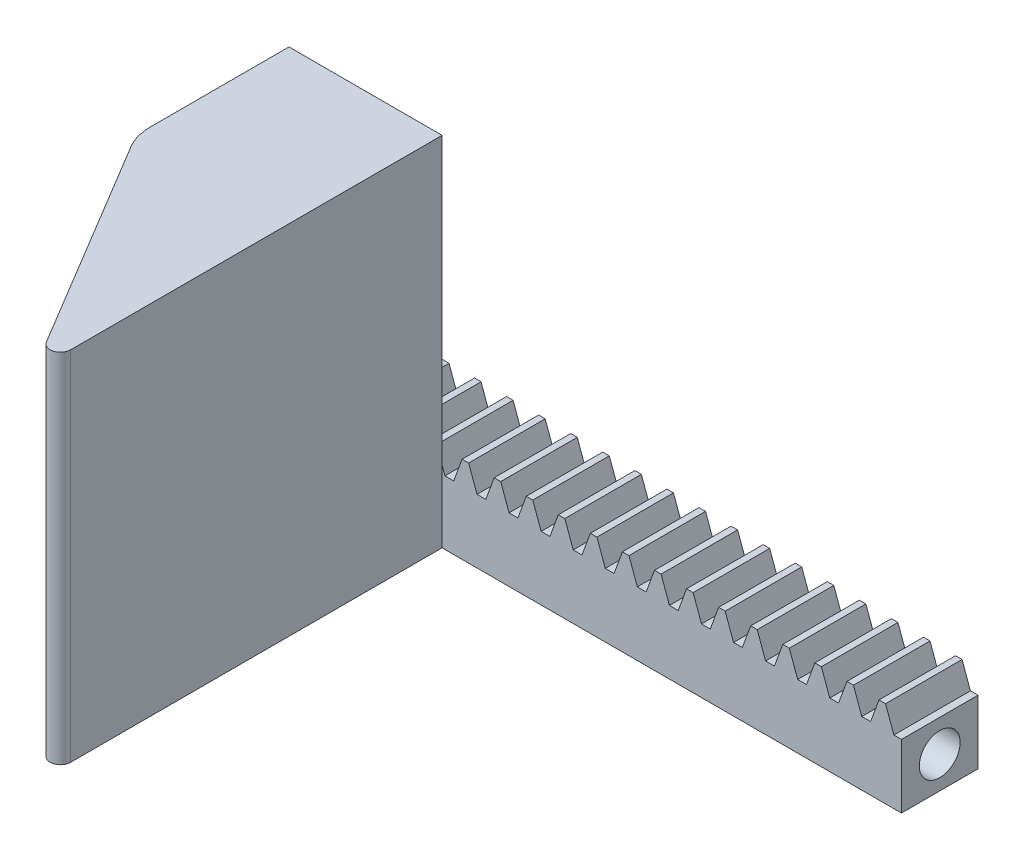
SolidWorks part; units mm, degrees
extrude "Blank" add sketch "BlankSke" against normal blind 15
sketch "BlankSke" plane through (0, 0, 0) normal (0, 0, 1) x (1, 0, 0)
  line L1 (0, 0) -> (120, 0)
  line L2 (0, 0) -> (0, 17)
  line L3 (0, 17) -> (120, 17)
  line L4 (120, 0) -> (120, 17)
  dimension "Length" = 120
  dimension "Blank_height" = 17
ref_plane "Plane1" through (0, 0, 0) normal (0, 0, 1) x (1, 0, 0)
ref_plane "Plane2" through (0, 0, 0) normal (0, 1, 0) x (1, 0, 0)
ref_plane "Plane3" through (0, 0, 0) normal (1, 0, 0) x (0, 0, -1)
other "Configuration Table"
sketch "HoldingSke" plane through (0, 0, 0) normal (0, 1, 0) x (1, 0, 0)
  line L0 (0, 0) -> (0.0696, 0.4951)
  line L1 (-15, 0) -> (100, 0) construction
  line L2 (0, 0) -> (-2.1039, 2.3779)
  line L3 (0, 0) -> (-11.863, 4.5341)
  line L4 (0, 0) -> (8.0624, 3.0949)
  line L5 (0, 0) -> (-23.7986, -8.8762)
  line L6 (0, 0) -> (-10.5278, -7.1032)
  line L9 (-71.009, 38.7566) -> (41.7541, 79.799)
  line L10 (-76.2, 4.3779) -> (-61.2, 4.3779)
  line L11 (0, 0) -> (-15, 0)
  line L12 (-76.2, 101.6) -> (-76.133, 101.6)
  line L13 (24.9733, 27.94) -> (52.9518, 28.4284)
  line L14 (24.9733, 27.94) -> (24.9743, 27.94)
  line L15 (24.9733, 27.94) -> (100.4006, 29.5858)
  circle A0 centre (0, 0) radius 19.05
  circle A1 centre (0, 0) radius 7.5
  circle A2 centre (0, 0) radius 12.7
  dimension "MPH" = 15
  dimension "Diameter" = 38.1
  dimension "Num_teeth" = 21
  dimension "Pitch" = 0.5
  dimension "Show_teeth" = 998
  dimension "Thickness" = 12.7
  dimension "Ap" = 20
  dimension "Pitch_height" = 15
  dimension "Width" = 15
  dimension "Backlash" = 0.067
  dimension "Addendum_fac" = 1
  dimension "Dedendum_fac" = 1.25
  dimension "Clearance_fac" = 0.25
  dimension "Dedendum_add" = 0.001
  dimension "Length" = 120
  dimension "Module" = 2
sketch "TooCutSkeIll" plane through (0, 0, 0) normal (0, 0, 1) x (1, 0, 0)
  line L0 (-2.4806, 16.9474) -> (-0.9819, 12.8296)
  line L1 (-0.5111, 12.5) -> (0.5111, 12.5)
  line L2 (0.9819, 12.8296) -> (2.4806, 16.9474)
  line L3 (120, 17) -> (0, 17) construction
  line L4 (0, 0) -> (0, 64.897) construction
  line L5 (-13.208, 15) -> (12.954, 15) construction
  line L6 (0, 0) -> (120, 0) construction
  line L7 (1.7718, 15) -> (1.7718, 48.7463) construction
  line L8 (-1.7718, 15) -> (-1.7718, 48.7463) construction
  line L9 (2.5558, 17) -> (2.5558, 17.0254)
  line L10 (-2.5558, 17) -> (-2.5558, 17.0254)
  line L11 (-2.5558, 17.0254) -> (2.5558, 17.0254)
  arc A0 (0.5111, 12.5) -> (0.9819, 12.8296) centre (0.5111, 13.001) ccw
  arc A1 (-0.9819, 12.8296) -> (-0.5111, 12.5) centre (-0.5111, 13.001) ccw
  arc A2 (2.5558, 17) -> (2.4806, 16.9474) centre (2.5558, 16.92) ccw
  arc A3 (-2.4806, 16.9474) -> (-2.5558, 17) centre (-2.5558, 16.92) ccw
  dimension "Pitch_height" = 15
  dimension "Addendum_plus" = 2.0254
  dimension "Pressure_angle" = 20
  dimension "Gap_width" = 3.5436
  dimension "Dedendum" = 2.5
extrude "ToothCutIll" [suppressed] cut sketch "TooCutSkeIll" against normal through all
sketch "TooCutSkeSim" plane through (0, 0, 0) normal (0, 0, 1) x (1, 0, 0)
  line L0 (0.8619, 12.5) -> (-0.8619, 12.5)
  line L1 (2.509, 17.0254) -> (0.8619, 12.5)
  line L2 (0, 17.4625) -> (0, 53.467) construction
  line L3 (2.509, 17.0254) -> (-2.509, 17.0254)
  line L6 (-2.509, 17.0254) -> (-0.8619, 12.5)
  line L9 (-1.7718, 15) -> (1.7718, 15) construction
  line L10 (0, 0) -> (120, 0) construction
  line L11 (1.7718, 15) -> (1.7718, 53.467) construction
  line L12 (-1.7718, 15) -> (-1.7718, 53.467) construction
  dimension "Pitch_height" = 15
  dimension "Addendum_plus" = 2.0254
  dimension "Pressure_angle" = 20
  dimension "Gap_width" = 3.5436
  dimension "Dedendum" = 2.5
extrude "ToothCutSim" cut sketch "TooCutSkeSim" against normal through all
pattern_linear "TeethCuts" count 20 spacing 6.2832 along (1, 0, 0) of "ToothCutIll", "ToothCutSim"
sketch "Esboço5" plane through (0, 0, 0) normal (0, -1, 0) x (1, 0, 0)
  line L0 (0, 0) -> (30, 0)
  line L1 (30, 0) -> (30, 72.7794)
  line L2 (26.285, 73.8084) -> (1.4251, 32.3751)
  line L3 (0, 27.2302) -> (0, 0)
  line L5 (0, 0) -> (120, 0) construction
  arc A0 (30, 72.7794) -> (26.285, 73.8084) centre (28, 72.7794) ccw
  arc A1 (1.4251, 32.3751) -> (0, 27.2302) centre (10, 27.2302) ccw
  point P10 (30, 80)
  point P13 (0, 30)
  dimension "D3" = 30
  dimension "D4" = 2
  dimension "D5" = 10
  dimension "D1" = 30
  dimension "D2" = 80
extrude "Ressalto-extrusão2" add sketch "Esboço5" against normal blind 70 separate body
sketch "Esboço8" plane through (0, 0, 0) normal (-1, 0, 0) x (0, 0, 1)
  line L0 (-15, 12.5) -> (0, 0) construction
  line L1 (0, 12.5) -> (-15, 0) construction
  circle A0 centre (-7.5, 6.25) radius 4
  dimension "D1" = 8
extrude "Corte-extrusão2" cut sketch "Esboço8" against normal up to next (120 mm away)
equation "' \"Module@HoldingSke\" = 6.35"
equation "' \"Num_teeth@HoldingSke\" = 12"
equation "' \"Ap@HoldingSke\" =  20"
equation "' \"Ap@HoldingSke\" = 20"
equation "' \"Width@HoldingSke\" = 0.25 * 25.4"
equation "' \"Show_teeth@HoldingSke\" = 500"
equation "' \"Backlash@HoldingSke\" = 0.009 * 25.4"
equation "' \"Addendum_fac@HoldingSke\" = 1.0"
equation "' \"Dedendum_fac@HoldingSke\" = 1.25"
equation "' \"Dedendum_add@HoldingSke\" = 0.00005 * 25.4"
equation "' \"Clearance_fac@HoldingSke\" = 0.25"
equation "' \"Pitch_height@HoldingSke\" = 1 * 25.4"
equation "' \"Length@HoldingSke\" = 4.71 * 25.4"
equation "\"Pitch@HoldingSke\" = 1 / \"Module@HoldingSke\""
equation "\"MPH@HoldingSke\" = \"Dedendum_fac@HoldingSke\" / \"Pitch@HoldingSke\" + 2 * \"Dedendum_add@HoldingSke\" + 0.002 * 25.4"
equation "\"MPH@HoldingSke\" = ((sgn( \"MPH@HoldingSke\" - \"Pitch_height@HoldingSke\")+1)*( \"MPH@HoldingSke\" - \"Pitch_height@HoldingSke\"))/2 + \"Pitch_height@HoldingSke\""
equation "\"Blank_height@BlankSke\" = \"Pitch_height@HoldingSke\" + \"Addendum_fac@HoldingSke\"  / \"Pitch@HoldingSke\" "
equation "\"Length@BlankSke\" =  \"Length@HoldingSke\""
equation "\"Face_width@Blank\" = \"Width@HoldingSke\""
equation "\"Pressure_angle@TooCutSkeIll\" = \"Ap@HoldingSke\""
equation "\"Addendum_plus@TooCutSkeIll\" =  \"Addendum_fac@HoldingSke\"  / \"Pitch@HoldingSke\" + 0.001 *25.4"
equation "\"Dedendum@TooCutSkeIll\" = \"Dedendum_fac@HoldingSke\"  / \"Pitch@HoldingSke\""
equation "\"Pitch_height@TooCutSkeIll\" =  \"MPH@HoldingSke\""
equation "\"Gap_width@TooCutSkeIll\" = 3.14159265 / 2 / \"Pitch@HoldingSke\" + 6 * \"Backlash@HoldingSke\""
equation "\"Pressure_angle@TooCutSkeSim\" = \"Ap@HoldingSke\""
equation "\"Addendum_plus@TooCutSkeSim\" =  \"Addendum_fac@HoldingSke\"  / \"Pitch@HoldingSke\" + 0.001 * 25.4"
equation "\"Dedendum@TooCutSkeSim\" = \"Dedendum_fac@HoldingSke\"  / \"Pitch@HoldingSke\""
equation "\"Pitch_height@TooCutSkeSim\" =  \"MPH@HoldingSke\""
equation "\"Gap_width@TooCutSkeSim\" = 3.14159265 / 2 / \"Pitch@HoldingSke\" + 6 * \"Backlash@HoldingSke\""
equation "\"Root_fillet@TooCutSkeIll\" = \"Clearance_fac@HoldingSke\" / \"Pitch@HoldingSke\" + \"Dedendum_add@HoldingSke\""
equation "\"Break_rad@TooCutSkeIll\" = 0.02 / \"Pitch@HoldingSke\" * 2"
equation "\"Linear_pitch@TeethCuts\" = 3.14159265 / \"Pitch@HoldingSke\""
equation "\"Num_teeth@HoldingSke\" = int( ( \"Length@HoldingSke\" + 0 ) / (3.14159265 / \"Pitch@HoldingSke\")) + 0.9999  + 1"
equation " \"Num_teeth@TeethCuts\" = int( \"Show_teeth@HoldingSke\" ) + 1"
equation " \"Num_teeth@TeethCuts\" = ((sgn( \"Num_teeth@TeethCuts\" - \"Num_teeth@HoldingSke\" )-1)*( \"Num_teeth@TeethCuts\" - \"Num_teeth@HoldingSke\" ))/-2+ \"Num_teeth@HoldingSke\""
equation " \"Num_teeth@TeethCuts\" = ((sgn( \"Num_teeth@TeethCuts\" - 2.0)+1)*( \"Num_teeth@TeethCuts\" - 2.0))/2 +2.0"
